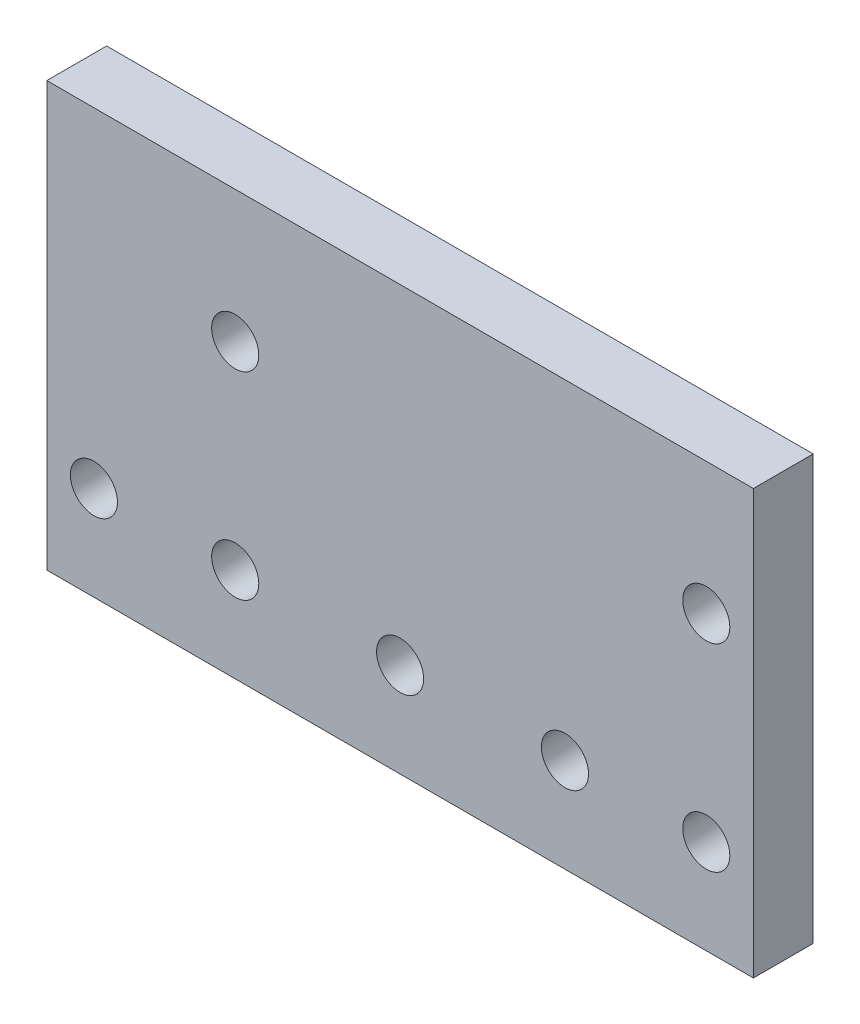
SolidWorks part; units mm, degrees
material "6061-T6 (SS)"
ref_plane "Front Plane" through (0, 0, 0) normal (0, 0, 1) x (1, 0, 0)
ref_plane "Top Plane" through (0, 0, 0) normal (0, 1, 0) x (1, 0, 0)
ref_plane "Right Plane" through (0, 0, 0) normal (1, 0, 0) x (0, 0, -1)
sketch "Sketch1" plane through (0, 0, 0) normal (0, 0, 1) x (1, 0, 0)
  line L0 (20, 31) -> (70, 31) construction
  line L1 (0, 0) -> (75, 0)
  line L2 (0, 0) -> (0, 45)
  line L3 (0, 45) -> (75, 45)
  line L4 (75, 0) -> (75, 45)
  line L5 (0, 10) -> (75, 10) construction
  circle A0 centre (20, 31) radius 2.5
  circle A1 centre (70, 31) radius 2.5
  circle A2 centre (5, 10) radius 2.5
  circle A3 centre (20, 10) radius 2.5
  circle A4 centre (55, 10) radius 2.5
  circle A5 centre (70, 10) radius 2.5
  circle A6 centre (37.5, 10) radius 2.5
  dimension "D6" = 5
  dimension "D9" = 5
  dimension "D1" = 75
  dimension "D2" = 45
  dimension "D3" = 20
  dimension "D4" = 31
  dimension "D5" = 50
  dimension "D7" = 10
  dimension "D8" = 5
  dimension "D10" = 5
  dimension "D11" = 15
  dimension "D12" = 15
extrude "Boss-Extrude1" add sketch "Sketch1" along normal blind 6.35
